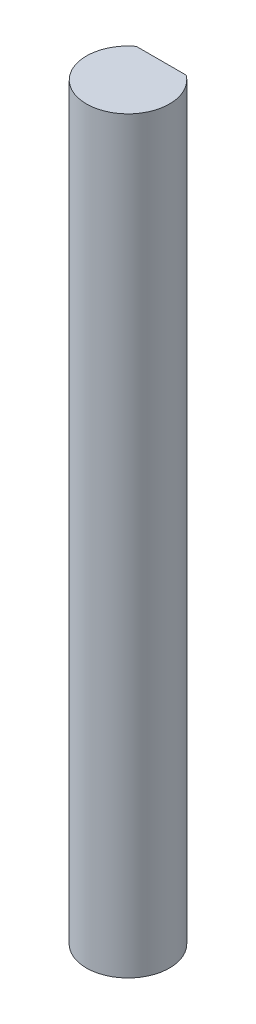
SolidWorks part; units mm, degrees
ref_plane "前视基准面" through (0, 0, 0) normal (0, 0, 1) x (1, 0, 0)
ref_plane "上视基准面" through (0, 0, 0) normal (0, 1, 0) x (1, 0, 0)
ref_plane "右视基准面" through (0, 0, 0) normal (1, 0, 0) x (0, 0, -1)
sketch "草图1" plane through (0, 0, 0) normal (0, 1, 0) x (1, 0, 0)
  line L0 (-1.5, 2) -> (1.5, 2)
  line L1 (0, 2) -> (0, -2.5) construction
  circle A0 centre (0, 0) radius 2.5
  dimension "D2" = 5
  dimension "D1" = 4.5
extrude "凸台-拉伸1" add sketch "草图1" along normal blind 45 contours L1 L0 A0 | L0 L1 A0
